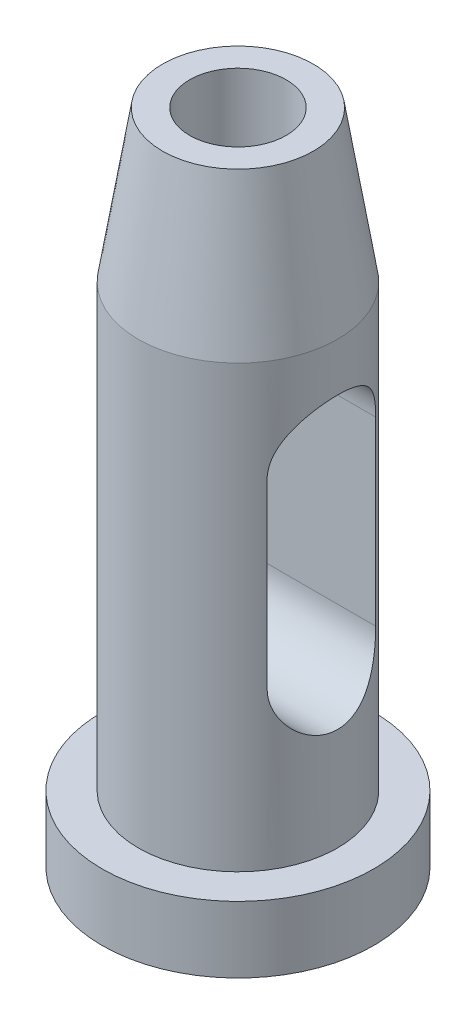
SolidWorks part; units mm, degrees
material "Galvanized Steel"
ref_plane "Front Plane" through (0, 0, 0) normal (0, 0, 1) x (1, 0, 0)
ref_plane "Top Plane" through (0, 0, 0) normal (0, 1, 0) x (1, 0, 0)
ref_plane "Right Plane" through (0, 0, 0) normal (1, 0, 0) x (0, 0, -1)
sketch "Sketch1" plane through (0, 0, 0) normal (1, 0, 0) x (0, 0, -1)
  line L0 (0, 0) -> (-22.5, 0)
  line L1 (-22.5, 0) -> (-22.5, 11)
  line L2 (-22.5, 11) -> (-16.5, 11)
  line L3 (-16.5, 11) -> (-16.5, 84)
  line L4 (-16.5, 84) -> (-12.5, 109)
  line L5 (-12.5, 109) -> (0, 109)
  line L6 (0, 109) -> (0, 0)
  dimension "D1" = 22.5
  dimension "D2" = 16.5
  dimension "D3" = 12.5
  dimension "D4" = 11
  dimension "D5" = 109
  dimension "D6" = 25
revolve "Revolve1" add sketch "Sketch1" angle 360 about L6
sketch "Sketch2" plane through (0, 0, 0) normal (1, 0, 0) x (0, 0, -1)
  line L0 (0, 37) -> (0, 67) construction
  line L1 (-9, 37) -> (-9, 67)
  line L2 (9, 37) -> (9, 67)
  line L3 (22.5, 11) -> (-22.5, 11) construction
  arc A0 (-9, 37) -> (9, 37) centre (0, 37) ccw
  arc A1 (9, 67) -> (-9, 67) centre (0, 67) ccw
  point P3 (0, 52)
  dimension "D3" = 9
  dimension "D1" = 26
  dimension "D2" = 30
extrude "Cut-Extrude1" cut sketch "Sketch2" against normal through all both and the other way through all
hole_wizard "Ø16.0mm Dowel Hole1" positions "3DSketch1" profile "Sketch3" hole size "Ø16.0" standard "ISO"
sketch3d "3DSketch1"
  line L0 (0, 84, 0) -> (0, 109, 0) construction
  point P0 (0, 109, 0)
sketch "Sketch3" plane through (0, 109, 0) normal (1, 0, 0) x (0, 0, 1)
  line L0 (0, 0) -> (0, 37.5)
  line L1 (0, 37.5) -> (8, 32.6931)
  line L2 (8, 32.6931) -> (8, 0)
  line L5 (8, 0) -> (0, 0)
  line L10 (0, 37.5) -> (-8, 32.6931) construction
  line L11 (0, -6.35) -> (0, 107.95) construction
  dimension "Hole Dia." = 16
  dimension "Hole Depth" = 37.5
  dimension "Drill Angle" = 118
